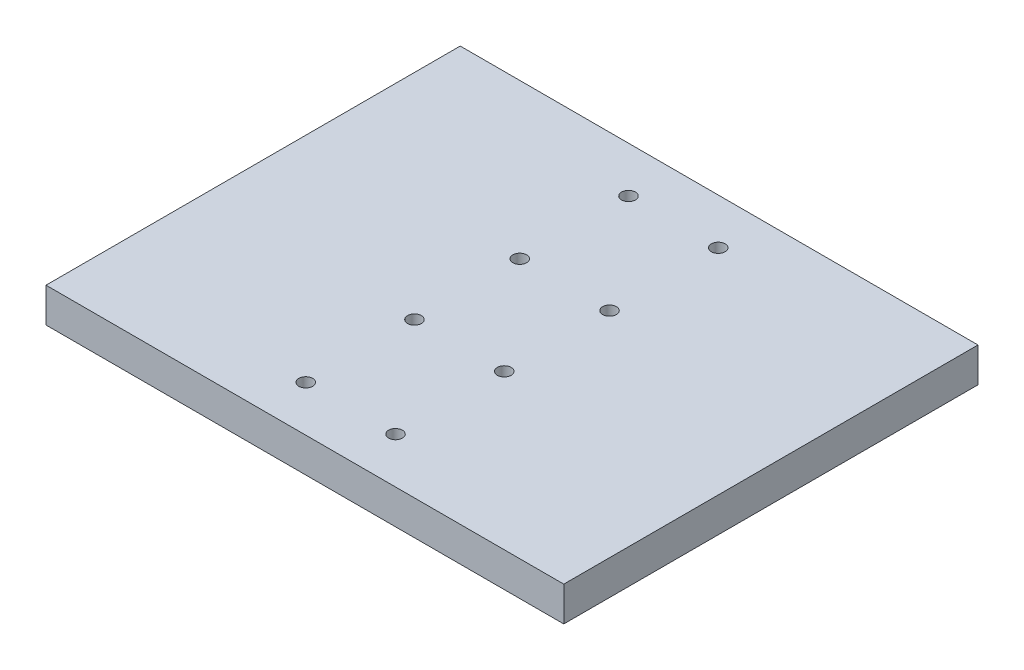
SolidWorks part; units mm, degrees
ref_plane "Ön Düzlem" through (0, 0, 0) normal (0, 0, 1) x (1, 0, 0)
ref_plane "Üst Düzlem" through (0, 0, 0) normal (0, 1, 0) x (1, 0, 0)
ref_plane "Sağ Düzlem" through (0, 0, 0) normal (1, 0, 0) x (0, 0, -1)
sketch "Sketch1" plane through (0, 0, 0) normal (0, 1, 0) x (1, 0, 0)
  line L0 (0, 31) -> (0, -31) construction
  line L1 (-75, -60) -> (75, -60)
  line L2 (-75, -60) -> (-75, 60)
  line L3 (-75, 60) -> (75, 60)
  line L4 (75, -60) -> (75, 60)
  line L5 (-75, -60) -> (75, 60) construction
  line L6 (-75, 60) -> (75, -60) construction
  line L7 (-13, 15.25) -> (13, 15.25) construction
  line L8 (-13, 15.25) -> (-13, 46.75) construction
  line L9 (-13, 46.75) -> (13, 46.75) construction
  line L10 (13, 15.25) -> (13, 46.75) construction
  line L11 (-13, 15.25) -> (13, 46.75) construction
  line L12 (-13, 46.75) -> (13, 15.25) construction
  line L13 (-13, -46.75) -> (13, -46.75) construction
  line L14 (-13, -46.75) -> (-13, -15.25) construction
  line L15 (-13, -15.25) -> (13, -15.25) construction
  line L16 (13, -46.75) -> (13, -15.25) construction
  line L17 (-13, -46.75) -> (13, -15.25) construction
  line L18 (-13, -15.25) -> (13, -46.75) construction
  line L19 (0, 60) -> (0, -60) construction
  circle A0 centre (-13, 46.75) radius 2
  circle A1 centre (13, 46.75) radius 2
  circle A2 centre (13, 15.25) radius 2
  circle A3 centre (-13, 15.25) radius 2
  circle A4 centre (-13, -15.25) radius 2
  circle A5 centre (13, -15.25) radius 2
  circle A6 centre (13, -46.75) radius 2
  circle A7 centre (-13, -46.75) radius 2
  point P0 (0, 0)
  point P6 (0, 31)
  point P11 (0, -31)
  point P16 (0, 0)
  point P19 (75, 0)
  point P30 (0, 0)
  point P31 (0, 60)
  point P32 (0, -60)
  dimension "D6" = 4
  dimension "D1" = 120
  dimension "D2" = 150
  dimension "D3" = 62
  dimension "D4" = 31.5
  dimension "D5" = 26
  dimension "D7" = 75
extrude "Boss-Extrude1" add sketch "Sketch1" along normal blind 10
